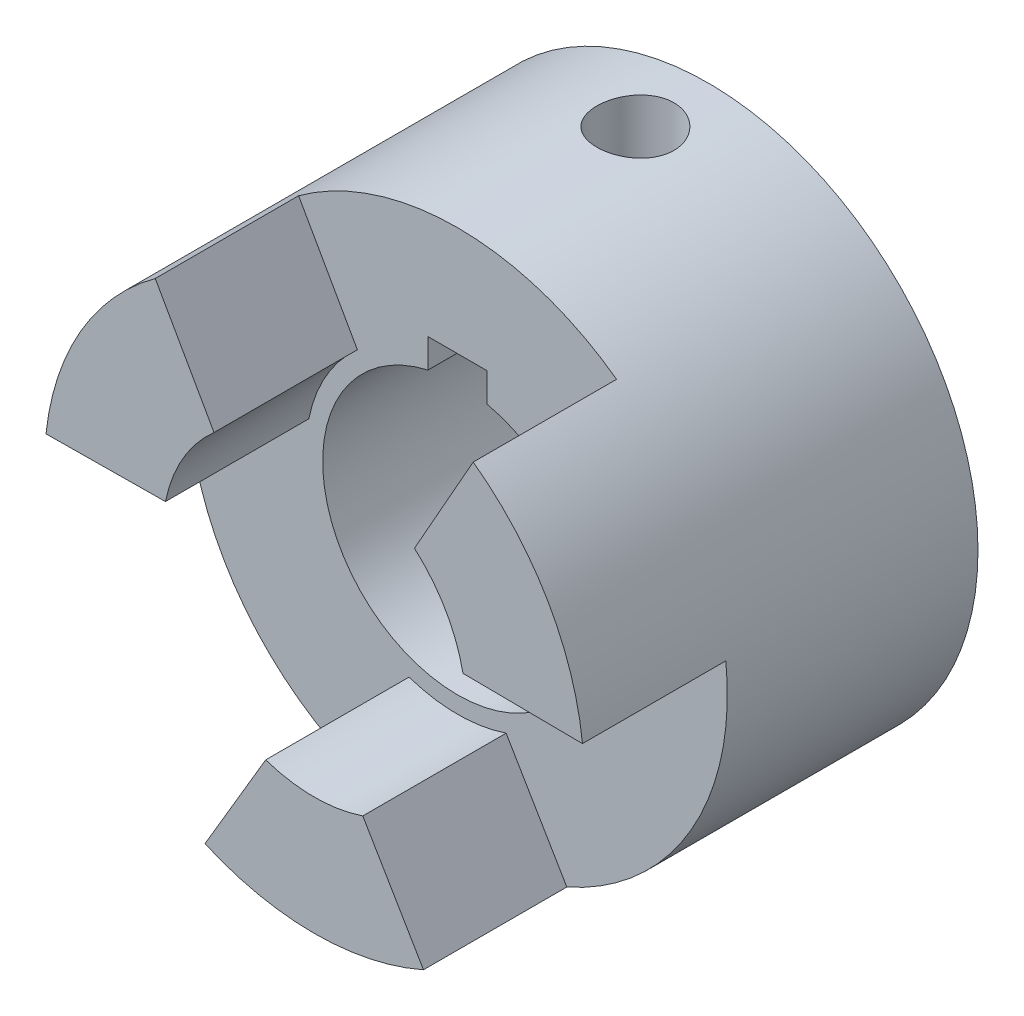
SolidWorks part; units mm, degrees
ref_plane "Płaszczyzna przednia" through (0, 0, 0) normal (0, 0, 1) x (1, 0, 0)
ref_plane "Płaszczyzna górna" through (0, 0, 0) normal (0, 1, 0) x (1, 0, 0)
ref_plane "Płaszczyzna prawa" through (0, 0, 0) normal (1, 0, 0) x (0, 0, -1)
sketch "Szkic1" plane through (0, 0, 0) normal (0, 0, 1) x (1, 0, 0)
  circle A0 centre (0, 0) radius 22.225
  dimension "D1" = 44.45
extrude "Dodanie-wyciągnięcie1" add sketch "Szkic1" along normal blind 20.65
sketch "Szkic2" plane through (0, 0, 20.65) normal (0, 0, 1) x (1, 0, 0)
  line L1 (-2.44, 13.2339) -> (2.44, 13.2339)
  line L2 (-2.44, 13.2339) -> (-2.44, 10.8439)
  line L4 (2.44, 13.2339) -> (2.44, 10.8439)
  arc A0 (-2.44, 10.8439) -> (2.44, 10.8439) centre (0, 0) ccw
  point P1 (0, 0)
  point P7 (1.7378, 10.9783)
  point P8 (0, 13.2339)
  dimension "D1" = 22.23
  dimension "D2" = 4.88
  dimension "D3" = 2.39
extrude "Wytnij-wyciągnięcie1" cut sketch "Szkic2" against normal up to next
sketch "Szkic3" plane through (0, 0, 20.65) normal (0, 0, 1) x (1, 0, 0)
  line L0 (-4, -11.8427) -> (-9, -20.3212)
  line L1 (0, 0) -> (0, -32.7464) construction
  line L2 (4, -11.8427) -> (9, -20.3212)
  circle A0 centre (0, 0) radius 22.225 construction
  circle A1 centre (0, 0) radius 22.225
  circle A2 centre (0, 0) radius 12.5
  point P6 (0, -31.2993)
  point P8 (0, -32.7464)
  circle M6 centre (0, 0) radius 22.225
  dimension "D1" = 25
  dimension "D2" = 9
  dimension "D3" = 4
extrude "Dodanie-wyciągnięcie2" add sketch "Szkic3" along normal blind 11.81 contours L1 A2 L0 M6 | A2 L1 A1 L2
pattern_circular "Szyk kołowy1" count 3 over 360 about axis through (0, 0, 0) along (0, 0, 1) of "Dodanie-wyciągnięcie2"
ref_plane "Płaszczyzna1" through (0, 22.225, 0) normal (0, 1, 0) x (1, 0, 0)
sketch "Szkic4" plane through (0, 22.225, 0) normal (0, 1, 0) x (1, 0, 0)
  line L0 (-2.44, 0) -> (2.44, 0) construction
  circle A0 centre (0, -6) radius 3.175
  dimension "D1" = 6.35
  dimension "D2" = 6
extrude "Wytnij-wyciągnięcie2" cut sketch "Szkic4" against normal blind 6.54
